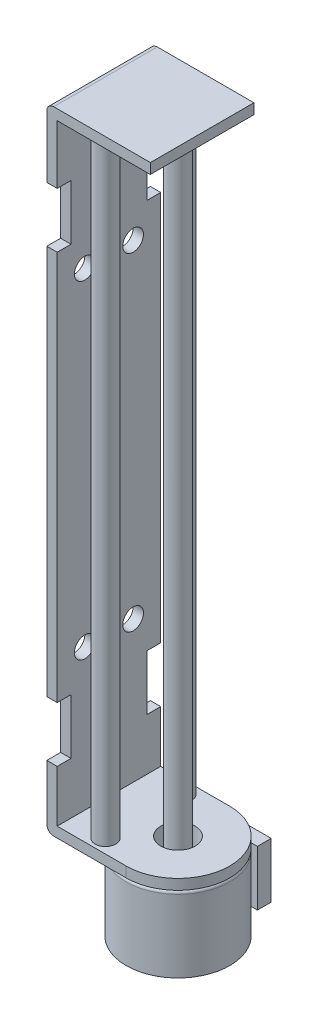
SolidWorks part; units mm, degrees
ref_plane "Front Plane" through (0, 0, 0) normal (0, 0, 1) x (1, 0, 0)
ref_plane "Top Plane" through (0, 0, 0) normal (0, 1, 0) x (1, 0, 0)
ref_plane "Right Plane" through (0, 0, 0) normal (1, 0, 0) x (0, 0, -1)
sketch "Sketch1" plane through (0, 0, 0) normal (0, 1, 0) x (1, 0, 0)
  circle A0 centre (0, 0) radius 7.5
  dimension "D1" = 15
extrude "Boss-Extrude1" add sketch "Sketch1" along normal blind 11
fillet "Fillet1" radius 0.5 1 edges at (0, 11, 7.5)
sketch "Sketch3" plane through (0, 11, 0) normal (0, 1, 0) x (1, 0, 0)
  line L0 (0, -7.5) -> (-10, -7.5)
  line L1 (-10, -7.5) -> (-10, 7.5)
  line L2 (-10, 7.5) -> (0, 7.5)
  circle A0 centre (0, 0) radius 7.5 construction
  arc A1 (0, 7.5) -> (0, -7.5) centre (0, 0) cw
  dimension "D1" = 7.5
  dimension "D2" = 10
extrude "Boss-Extrude2" add sketch "Sketch3" along normal blind 1.5
sketch "Sketch5" plane through (0, 11, 0) normal (0, -1, 0) x (1, 0, 0)
  line L0 (-10, -7.5) -> (-11.5, -7.5)
  line L1 (-11.5, -7.5) -> (-11.5, 7.5)
  line L2 (-11.5, 7.5) -> (-10, 7.5)
  line L3 (-10, 7.5) -> (-10, -7.5)
  dimension "D1" = 1.5
extrude "Boss-Extrude3" add sketch "Sketch5" against normal blind 90
fillet "Fillet2" radius 1 1 edges at (-11.5, 11, 0)
sketch "Sketch7" plane through (-11.5, 0, 0) normal (-1, 0, 0) x (0, 0, 1)
  line L0 (7.5, 101) -> (7.5, 102.5)
  line L1 (7.5, 102.5) -> (-7.5, 102.5)
  line L2 (-7.5, 102.5) -> (-7.5, 101)
  line L3 (-7.5, 101) -> (7.5, 101)
  dimension "D1" = 1.5
extrude "Boss-Extrude4" add sketch "Sketch7" against normal blind 15
fillet "Fillet3" radius 1 1 edges at (-11.5, 102.5, 0)
sketch "Sketch8" plane through (0, 12.5, 0) normal (0, 1, 0) x (1, 0, 0)
  circle A0 centre (0, 0) radius 2.5
  dimension "D1" = 5
extrude "Cut-Extrude1" cut sketch "Sketch8" against normal blind 10
sketch "Sketch9" plane through (0, 12.5, 0) normal (0, 1, 0) x (1, 0, 0)
  line L0 (-10, 7.5) -> (-10, -7.5) construction
  line L1 (-10, -7.5) -> (0, -7.5) construction
  line L2 (0, 7.5) -> (-10, 7.5) construction
  circle A0 centre (-5, 5.5) radius 1.5
  circle A1 centre (-5, -5.5) radius 1.5
  point P8 (-5, -7.5)
  dimension "D1" = 3
  dimension "D2" = 3
  dimension "D3" = 5
  dimension "D4" = 5
  dimension "D5" = 2
  dimension "D6" = 2
extrude "Boss-Extrude5" add sketch "Sketch9" along normal blind 90
sketch "Sketch10" plane through (0, 2.5, 0) normal (0, 1, 0) x (1, 0, 0)
  circle A0 centre (0, 0) radius 1.5
  dimension "D1" = 3
extrude "Boss-Extrude6" add sketch "Sketch10" along normal blind 99
sketch "Sketch11" plane through (-11.5, 0, 0) normal (-1, 0, 0) x (0, 0, 1)
  line L0 (7.5, 101.5) -> (-7.5, 101.5) construction
  line L1 (7.5, 101.5) -> (7.5, 12) construction
  line L2 (-7.5, 101.5) -> (-7.5, 12) construction
  line L3 (-7.5, 12) -> (7.5, 12) construction
  circle A0 centre (-3.5, 80.5) radius 1.5
  circle A1 centre (3.5, 80.5) radius 1.5
  circle A2 centre (-3.5, 33) radius 1.5
  circle A3 centre (3.5, 33) radius 1.5
  dimension "D1" = 3
  dimension "D2" = 3
  dimension "D3" = 3
  dimension "D4" = 3
  dimension "D5" = 21
  dimension "D6" = 21
  dimension "D7" = 4
  dimension "D8" = 4
  dimension "D9" = 4
  dimension "D10" = 4
  dimension "D11" = 21
  dimension "D12" = 21
extrude "Cut-Extrude2" cut sketch "Sketch11" against normal blind 2
sketch "Sketch12" plane through (-11.5, 0, 0) normal (-1, 0, 0) x (0, 0, 1)
  line L0 (7.5, 101.5) -> (7.5, 12) construction
  line L1 (5.5, 20) -> (7.5, 20)
  line L2 (5.5, 20) -> (5.5, 28)
  line L3 (5.5, 28) -> (7.5, 28)
  line L4 (7.5, 20) -> (7.5, 28)
  line L5 (5.5, 20) -> (7.5, 28) construction
  line L6 (5.5, 28) -> (7.5, 20) construction
  line L7 (-7.5, 12) -> (7.5, 12) construction
  line L8 (-7.5, 101.5) -> (-7.5, 12) construction
  line L9 (-5.5, 20) -> (-7.5, 20)
  line L10 (-5.5, 20) -> (-5.5, 28)
  line L11 (-5.5, 28) -> (-7.5, 28)
  line L12 (-7.5, 20) -> (-7.5, 28)
  line L13 (-5.5, 20) -> (-7.5, 28) construction
  line L14 (-5.5, 28) -> (-7.5, 20) construction
  line L16 (7.5, 84.5) -> (5.5, 84.5)
  line L17 (7.5, 84.5) -> (7.5, 92.5)
  line L18 (7.5, 92.5) -> (5.5, 92.5)
  line L19 (5.5, 84.5) -> (5.5, 92.5)
  line L20 (7.5, 84.5) -> (5.5, 92.5) construction
  line L21 (7.5, 92.5) -> (5.5, 84.5) construction
  line L22 (-5.5, 84.5) -> (-7.5, 84.5)
  line L23 (-5.5, 84.5) -> (-5.5, 92.5)
  line L24 (-5.5, 92.5) -> (-7.5, 92.5)
  line L25 (-7.5, 84.5) -> (-7.5, 92.5)
  line L26 (-5.5, 84.5) -> (-7.5, 92.5) construction
  line L27 (-5.5, 92.5) -> (-7.5, 84.5) construction
  point P0 (6.5, 24)
  point P9 (-6.5, 24)
  point P16 (6.5, 88.5)
  point P21 (-6.5, 88.5)
  dimension "D1" = 2
  dimension "D2" = 8
  dimension "D3" = 8
  dimension "D4" = 2
  dimension "D5" = 8
  dimension "D6" = 8
  dimension "D7" = 8
  dimension "D8" = 2
  dimension "D9" = 2
  dimension "D10" = 8
  dimension "D11" = 72.5
  dimension "D12" = 72.5
extrude "Cut-Extrude3" cut sketch "Sketch12" against normal blind 2
sketch "Sketch13" plane through (0, 0, -7.5) normal (0, 0, 1) x (1, 0, 0)
  line L1 (4, 1.468) -> (-4, 1.468)
  line L2 (4, 1.468) -> (4, 9.468)
  line L3 (4, 9.468) -> (-4, 9.468)
  line L4 (-4, 1.468) -> (-4, 9.468)
  line L5 (4, 1.468) -> (-4, 9.468) construction
  line L6 (4, 9.468) -> (-4, 1.468) construction
  point P0 (0, 5.468)
  dimension "D1" = 8
  dimension "D2" = 8
extrude "Boss-Extrude7" add sketch "Sketch13" against normal blind 2 separate body
